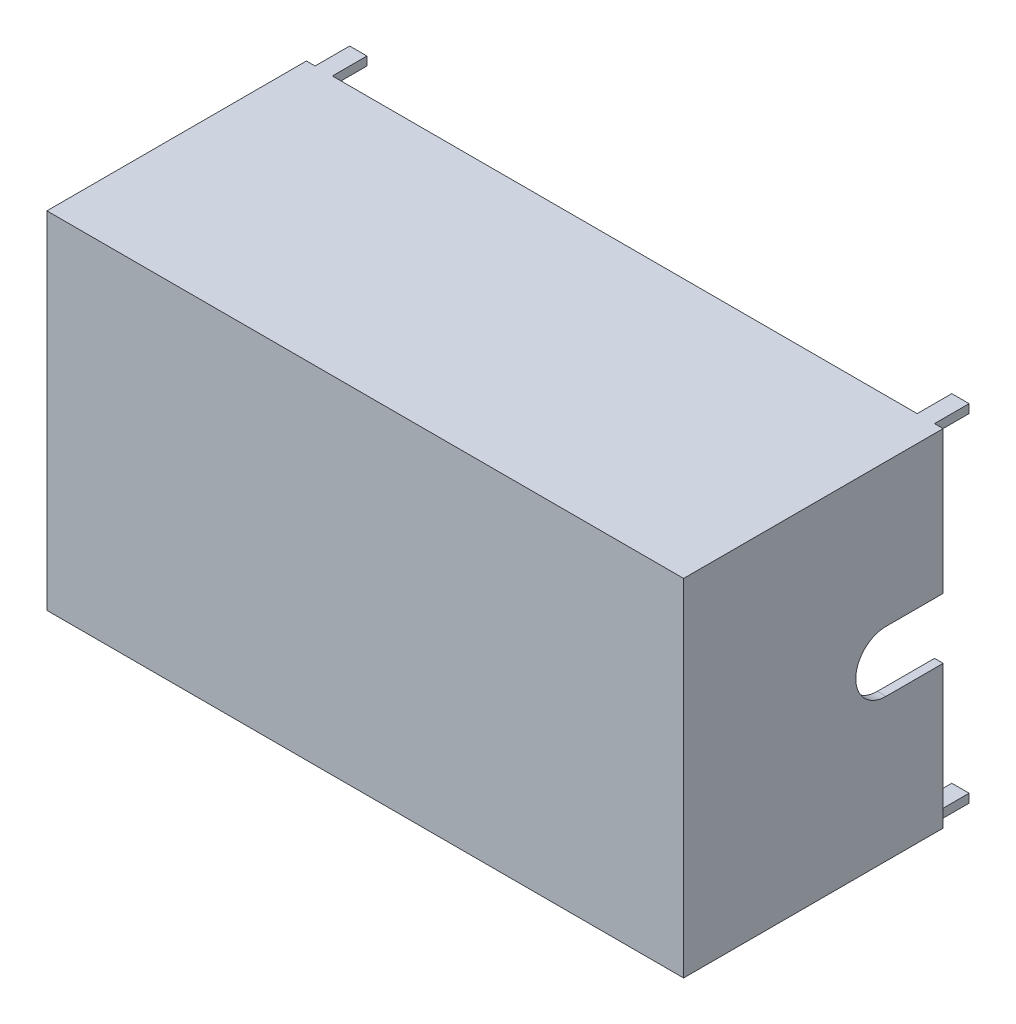
SolidWorks part; units mm, degrees
ref_plane "Face" through (0, 0, 0) normal (0, 0, 1) x (1, 0, 0)
ref_plane "Dessus" through (0, 0, 0) normal (0, 1, 0) x (1, 0, 0)
ref_plane "Droite" through (0, 0, 0) normal (1, 0, 0) x (0, 0, -1)
sketch "Esquisse1" plane through (0, 0, 0) normal (0, 0, 1) x (1, 0, 0)
  line L3 (-73.5423, -3.4132) -> (-37.7423, -3.4132)
  line L7 (-73.5423, 15.5868) -> (-73.5423, -3.4132)
  line L10 (-37.7423, 15.5868) -> (-73.5423, 15.5868)
  line L11 (-37.2423, 16.0868) -> (-74.0423, 16.0868)
  line L13 (-37.7423, -3.4132) -> (-37.7423, 15.5868)
  line L14 (-37.2423, -3.9132) -> (-37.2423, 16.0868)
  line L15 (-74.0423, -3.9132) -> (-37.2423, -3.9132)
  line L16 (-74.0423, 16.0868) -> (-74.0423, -3.9132)
  dimension "D5" = 0.5
extrude "Base-Extrusion" add sketch "Esquisse1" along normal blind 14
sketch "Esquisse2" plane through (0, 0, 14) normal (0, 0, 1) x (1, 0, 0)
  line L4 (-37.2423, -3.9132) -> (-37.2423, 16.0868)
  line L5 (-37.2423, 16.0868) -> (-74.0423, 16.0868)
  line L6 (-74.0423, 16.0868) -> (-74.0423, -3.9132)
  line L7 (-74.0423, -3.9132) -> (-37.2423, -3.9132)
  line L8 (-37.2423, -3.9132) -> (-37.2423, 16.0868)
  line L9 (-37.2423, 16.0868) -> (-74.0423, 16.0868)
  line L10 (-74.0423, 16.0868) -> (-74.0423, -3.9132)
  line L11 (-74.0423, -3.9132) -> (-37.2423, -3.9132)
  dimension "D1" = 0
extrude "Boss.-Extru.1" add sketch "Esquisse2" along normal blind 1
sketch "Esquisse3" plane through (-37.2423, 0, 0) normal (1, 0, 0) x (0, 0, -1)
  line L0 (0.676, 7.8368) -> (0.676, 4.3368)
  line L1 (-3.3, 7.8368) -> (0.676, 7.8368)
  line L2 (-3.3, 4.3368) -> (0.676, 4.3368)
  arc A0 (-3.3, 7.8368) -> (-3.3, 4.3368) centre (-3.3, 6.0868) ccw
  dimension "D1" = 3.5
extrude "Enlèv. mat.-Extru.1" cut sketch "Esquisse3" against normal through all
sketch "Esquisse4" plane through (0, 0, 0) normal (0, 0, -1) x (-1, 0, 0)
  line L0 (37.7423, 16.0868) -> (37.7423, 15.5868)
  line L1 (38.7423, 16.0868) -> (38.7423, 15.5868)
  line L2 (37.2423, 7.8368) -> (37.2423, 16.0868) construction
  line L3 (37.7423, 15.5868) -> (73.5423, 15.5868) construction
  line L4 (37.2423, 16.0868) -> (74.0423, 16.0868) construction
  line L5 (37.7423, 15.5868) -> (38.7423, 15.5868)
  line L6 (37.7423, 16.0868) -> (38.7423, 16.0868)
  line L7 (72.5423, 15.5868) -> (72.5423, 16.0868)
  line L8 (73.5423, 15.5868) -> (73.5423, 16.0868)
  line L9 (72.5423, 16.0868) -> (73.5423, 16.0868)
  line L10 (72.5423, 15.5868) -> (73.5423, 15.5868)
  line L11 (74.0423, 16.0868) -> (74.0423, 7.8368) construction
  line L12 (75.547, 6.0868) -> (35.4848, 6.0868) construction
  line L13 (74.0423, 6.0868) -> (73.5423, 6.0868) construction
  line L15 (72.5423, -3.9132) -> (73.5423, -3.9132)
  line L16 (73.5423, -3.4132) -> (73.5423, -3.9132)
  line L17 (72.5423, -3.4132) -> (72.5423, -3.9132)
  line L18 (37.7423, -3.9132) -> (38.7423, -3.9132)
  line L19 (37.7423, -3.4132) -> (38.7423, -3.4132)
  line L20 (38.7423, -3.9132) -> (38.7423, -3.4132)
  line L21 (37.7423, -3.9132) -> (37.7423, -3.4132)
  line L23 (72.5423, -3.4132) -> (73.5423, -3.4132)
  dimension "D1" = 0.5
  dimension "D2" = 1
  dimension "D3" = 0.5
  dimension "D4" = 1
  dimension "D5" = 0.5
extrude "Boss.-Extru.2" add sketch "Esquisse4" along normal blind 2
